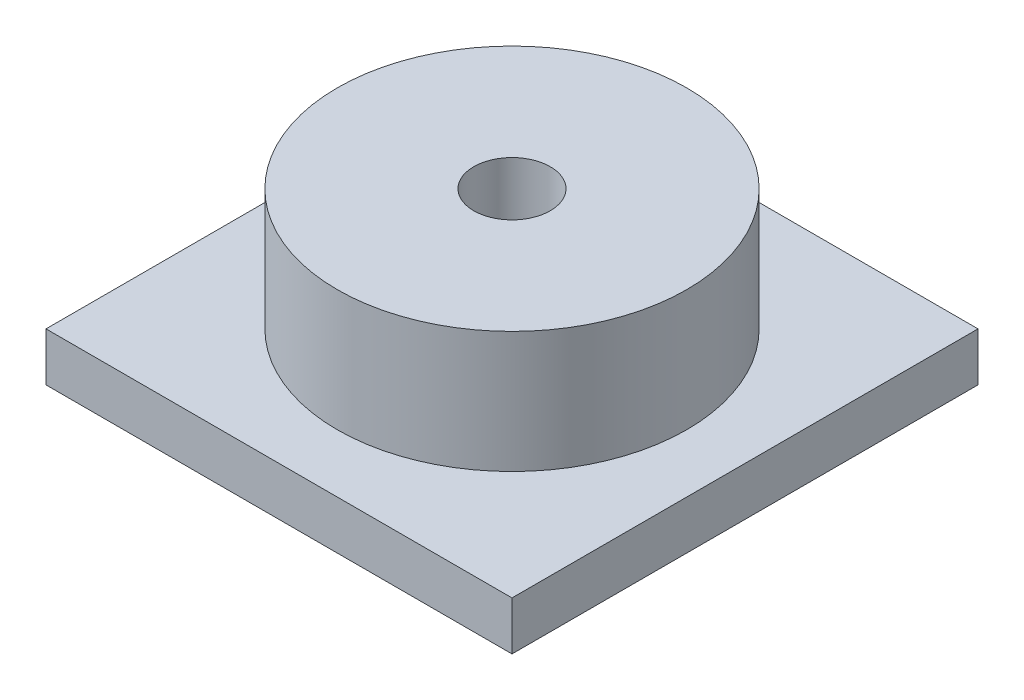
SolidWorks part; units mm, degrees
ref_plane "Front Plane" through (0, 0, 0) normal (0, 0, 1) x (1, 0, 0)
ref_plane "Top Plane" through (0, 0, 0) normal (0, 1, 0) x (1, 0, 0)
ref_plane "Right Plane" through (0, 0, 0) normal (1, 0, 0) x (0, 0, -1)
sketch "Sketch1" plane through (0, 0, 0) normal (0, 1, 0) x (1, 0, 0)
  line L1 (0, 0) -> (24.384, 0)
  line L2 (0, 0) -> (0, -24.384)
  line L3 (0, -24.384) -> (24.384, -24.384)
  line L4 (24.384, 0) -> (24.384, -24.384)
  dimension "D1" = 24.384
  dimension "D2" = 24.384
extrude "Boss-Extrude1" add sketch "Sketch1" along normal blind 2.54
sketch "Sketch2" plane through (0, 2.54, 0) normal (0, 1, 0) x (1, 0, 0)
  line L1 (0, 0) -> (0, -24.384) construction
  line L2 (24.384, 0) -> (0, 0) construction
  circle A0 centre (12.192, -12.192) radius 9.144
  point P2 (0, 0)
  point P3 (0, 0)
  point P4 (0, 0)
  point P5 (0, 0)
  dimension "D1" = 18.288
  dimension "D2" = 12.192
  dimension "D3" = 12.192
extrude "Boss-Extrude2" add sketch "Sketch2" along normal blind 6.35
sketch "Sketch3" plane through (0, 8.89, 0) normal (0, 1, 0) x (1, 0, 0)
  circle A0 centre (12.192, -12.192) radius 2
  dimension "D1" = 4
extrude "Cut-Extrude1" cut sketch "Sketch3" against normal through all
